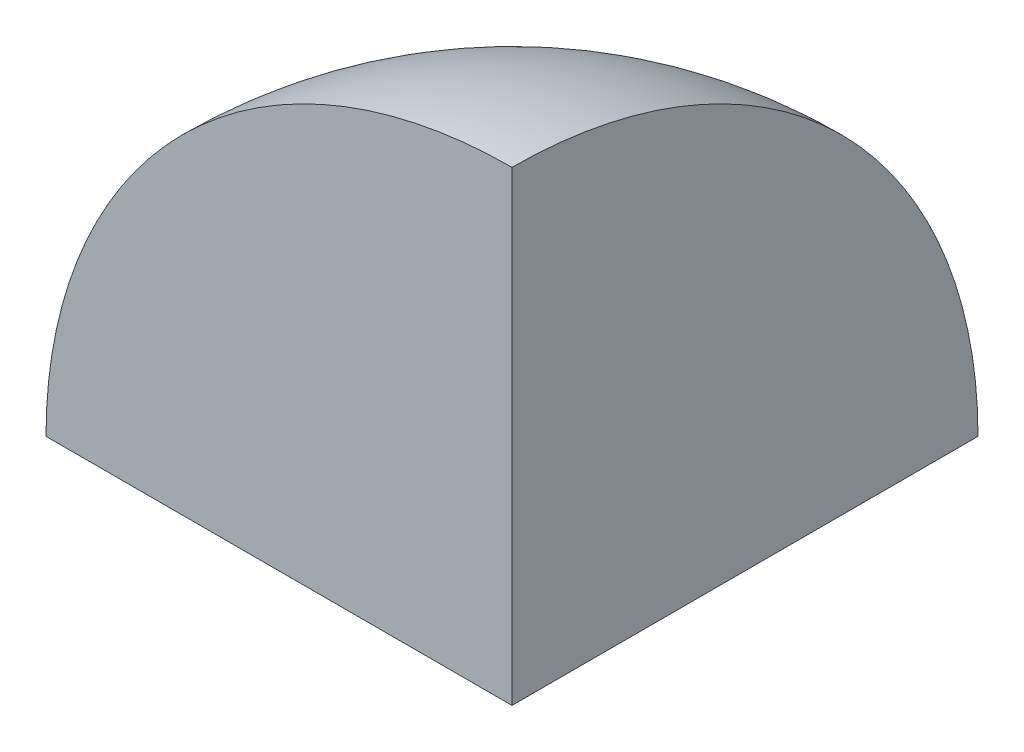
SolidWorks part; units mm, degrees
other "Камера1"
ref_plane "Спереди" through (0, 0, 0) normal (0, 0, 1) x (1, 0, 0)
ref_plane "Сверху" through (0, 0, 0) normal (0, 1, 0) x (1, 0, 0)
ref_plane "Справа" through (0, 0, 0) normal (1, 0, 0) x (0, 0, -1)
sketch "Эскиз2" plane through (0, 0, 0) normal (0, 1, 0) x (1, 0, 0)
  line L1 (13.435, -13.435) -> (-13.435, -13.435)
  line L2 (13.435, -13.435) -> (13.435, 13.435)
  line L3 (13.435, 13.435) -> (-13.435, 13.435)
  line L4 (-13.435, -13.435) -> (-13.435, 13.435)
  line L5 (13.435, -13.435) -> (-13.435, 13.435) construction
  line L6 (13.435, 13.435) -> (-13.435, -13.435) construction
  point P0 (0, 0)
  dimension "D1" = 38
  dimension "D2" = 26.8701
ref_plane "Плоскость1" through (0, 26.87, 0) normal (0, 1, 0) x (1, 0, 0)
ref_plane "Плоскость2" through (0, 0, -13.435) normal (0, 0, 1) x (1, 0, 0)
ref_plane "Плоскость3" through (-13.435, 0, 0) normal (1, 0, 0) x (0, 0, -1)
sketch "Эскиз5" plane through (-13.435, 0, 0) normal (1, 0, 0) x (0, 0, -1)
  line L0 (-10.565, 26.87) -> (37.435, 26.87)
  line L1 (55, 26.87) -> (-55, 26.87) construction
  line L2 (-10.565, 26.87) -> (37.435, 26.87) construction
  arc A0 (37.435, 26.87) -> (-10.565, 26.87) centre (13.435, 26.87) ccw
  point P0 (13.435, 26.87)
  dimension "D1" = 24
revolve "Повернуть1" add sketch "Эскиз5" angle 360 about L2
extrude "Бобышка-Вытянуть1" [suppressed] add sketch "Эскиз2" along normal blind 26.87
pattern_linear "Линейный массив1" [suppressed] count 2 spacing 26.87 count 2 spacing 26.87
sketch "Эскиз6" plane through (0, 0, -13.435) normal (0, 0, 1) x (1, 0, 0)
  line L0 (26.4, 26.87) -> (-26.4, 26.87) construction
  line L1 (11.565, 26.87) -> (10.565, 26.87) construction
  line L2 (11.565, 26.87) -> (10.565, 26.87)
  arc A0 (11.565, 26.87) -> (2.5733, 44.7512) centre (-10.7103, 26.87) ccw
  arc A1 (10.565, 26.87) -> (2.5733, 44.7512) centre (-13.435, 26.87) ccw
  circle A2 centre (-13.435, 26.87) radius 24 construction
  dimension "D1" = 1
revolve "Повернуть5" add sketch "Эскиз6" angle 360 about L1
other "Сечение1"
other "Сечение3"
other "Сечение7"
equation "\"x\"= \"D2@Эскиз2\""
equation "\"dx\"= \"D2@Эскиз2\" * 1.5"
